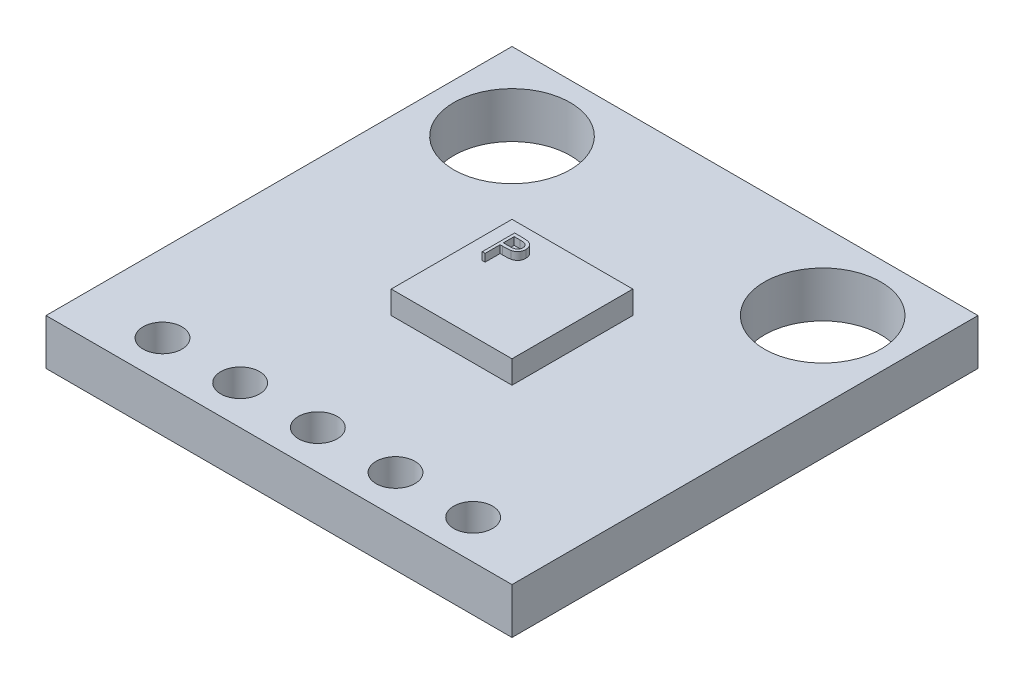
SolidWorks part; units mm, degrees
ref_plane "Front Plane" through (0, 0, 0) normal (0, 0, 1) x (1, 0, 0)
ref_plane "Top Plane" through (0, 0, 0) normal (0, 1, 0) x (1, 0, 0)
ref_plane "Right Plane" through (0, 0, 0) normal (1, 0, 0) x (0, 0, -1)
sketch "Sketch1" plane through (0, 0, 0) normal (0, 1, 0) x (1, 0, 0)
  line L1 (-7.62, 7.62) -> (7.62, 7.62)
  line L2 (-7.62, 7.62) -> (-7.62, -7.62)
  line L3 (-7.62, -7.62) -> (7.62, -7.62)
  line L4 (7.62, 7.62) -> (7.62, -7.62)
  line L5 (-7.62, 7.62) -> (7.62, -7.62) construction
  line L6 (-7.62, -7.62) -> (7.62, 7.62) construction
  point P0 (0, 0)
  dimension "D1" = 15.24
  dimension "D2" = 15.24
extrude "Boss-Extrude1" add sketch "Sketch1" along normal blind 1.5
sketch "Sketch2" plane through (0, 1.5, 0) normal (0, 1, 0) x (1, 0, 0)
  line L0 (-7.62, 5.08) -> (7.62, 5.08) construction
  line L1 (-7.62, 7.62) -> (-7.62, -7.62) construction
  line L2 (7.62, -7.62) -> (7.62, 7.62) construction
  line L3 (-7.62, -6.35) -> (7.62, -6.35) construction
  line L4 (7.62, 7.62) -> (-7.62, 7.62) construction
  line L5 (-7.62, -7.62) -> (7.62, -7.62) construction
  line L6 (0, -7.62) -> (0, 7.62) construction
  circle A0 centre (-5.08, 5.08) radius 1.905
  circle A1 centre (5.08, 5.08) radius 1.905
  circle A2 centre (5.08, -6.35) radius 0.635
  circle A3 centre (2.54, -6.35) radius 0.635
  circle A4 centre (0, -6.35) radius 0.635
  circle A5 centre (-2.54, -6.35) radius 0.635
  circle A6 centre (-5.08, -6.35) radius 0.635
  dimension "D1" = 3.81
  dimension "D2" = 3.81
  dimension "D3" = 1.27
  dimension "D4" = 1.27
  dimension "D5" = 1.27
  dimension "D6" = 1.27
  dimension "D7" = 1.27
  dimension "D8" = 2.54
  dimension "D9" = 2.54
  dimension "D10" = 2.54
  dimension "D11" = 2.54
  dimension "D12" = 2.54
  dimension "D13" = 2.54
  dimension "D14" = 2.54
  dimension "D15" = 1.27
extrude "Cut-Extrude1" cut sketch "Sketch2" against normal through all
sketch "Sketch3" plane through (0, 1.5, 0) normal (0, 1, 0) x (1, 0, 0)
  line L1 (-1.975, -1.975) -> (1.975, -1.975)
  line L2 (-1.975, -1.975) -> (-1.975, 1.975)
  line L3 (-1.975, 1.975) -> (1.975, 1.975)
  line L4 (1.975, -1.975) -> (1.975, 1.975)
  line L5 (-1.975, -1.975) -> (1.975, 1.975) construction
  line L6 (-1.975, 1.975) -> (1.975, -1.975) construction
  point P0 (0, 0)
  dimension "D1" = 3.95
  dimension "D2" = 3.95
extrude "Boss-Extrude2" add sketch "Sketch3" along normal blind 0.75
sketch "Sketch4" plane through (0, 2.25, 0) normal (0, 1, 0) x (1, 0, 0)
  text T0 "P" font "Century Gothic" height in points 4
extrude "Boss-Extrude3" add sketch "Sketch4" along normal blind 0.25
